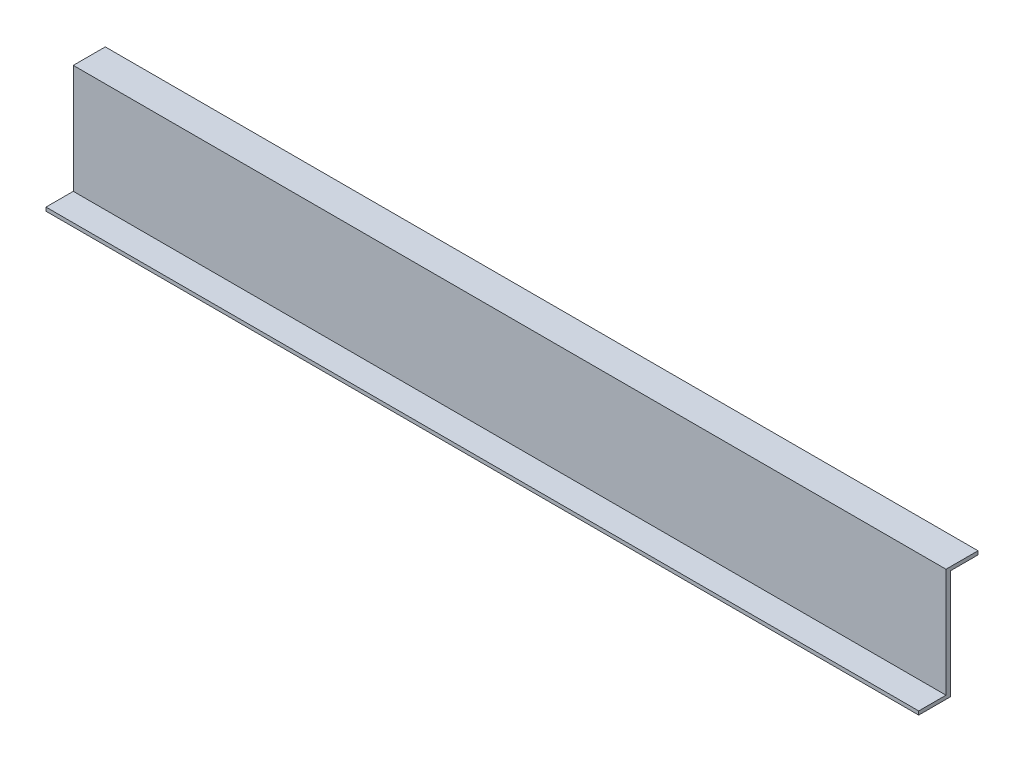
SolidWorks part; units mm, degrees
ref_plane "Front Plane" through (0, 0, 0) normal (0, 0, 1) x (1, 0, 0)
ref_plane "Top Plane" through (0, 0, 0) normal (0, 1, 0) x (1, 0, 0)
ref_plane "Right Plane" through (0, 0, 0) normal (1, 0, 0) x (0, 0, -1)
sketch "Sketch2" plane through (0, 0, 0) normal (0, 0, 1) x (1, 0, 0)
  line L1 (0, 0) -> (609.6, 0)
  line L2 (0, 0) -> (0, 78.74)
  line L3 (0, 78.74) -> (609.6, 78.74)
  line L4 (609.6, 0) -> (609.6, 78.74)
  dimension "D1" = 78.74
  dimension "D2" = 609.6
extrude "Boss-Extrude1" add sketch "Sketch2" along normal blind 44.704
sketch "Sketch4" plane through (609.6, 0, 0) normal (1, 0, 0) x (0, 0, -1)
  line L0 (-25.654, 2.54) -> (-25.654, 78.74)
  line L1 (-44.704, 78.74) -> (0, 78.74) construction
  line L2 (-25.654, 78.74) -> (-3.302, 78.74)
  line L3 (-3.302, 78.74) -> (-3.302, 76.2)
  line L4 (-3.302, 76.2) -> (-22.352, 76.2)
  line L5 (-22.352, 76.2) -> (-22.352, 0)
  line L6 (-44.704, 0) -> (0, 0) construction
  line L7 (-22.352, 0) -> (-44.704, 0)
  line L8 (-44.704, 0) -> (-44.704, 2.54)
  line L9 (-44.704, 0) -> (-44.704, 78.74) construction
  line L10 (-44.704, 2.54) -> (-25.654, 2.54)
  line L11 (-3.302, 78.74) -> (0, 78.74)
  line L12 (0, 78.74) -> (0, 0)
  line L13 (0, 0) -> (-22.352, 0)
  line L14 (-22.352, 76.2) -> (-3.302, 76.2)
  line L15 (-3.302, 78.74) -> (0, 78.74)
  line L16 (-44.704, 2.54) -> (-44.704, 78.74)
  line L17 (-44.704, 78.74) -> (-25.654, 78.74)
  line L18 (-25.654, 2.54) -> (-44.704, 2.54)
  line M3 (0, 0) -> (0, 78.74)
  line M4 (0, 78.74) -> (-44.704, 78.74)
  line M5 (-44.704, 78.74) -> (-44.704, 0)
  line M6 (-44.704, 0) -> (0, 0)
  dimension "D1" = 3.302
  dimension "D2" = 2.54
  dimension "D3" = 2.54
  dimension "D4" = 22.352
  dimension "D5" = 22.352
extrude "Cut-Extrude1" cut sketch "Sketch4" against normal through all contours L10 L0 M5 M4 | L4 L5 L3 M6 M3 M4
